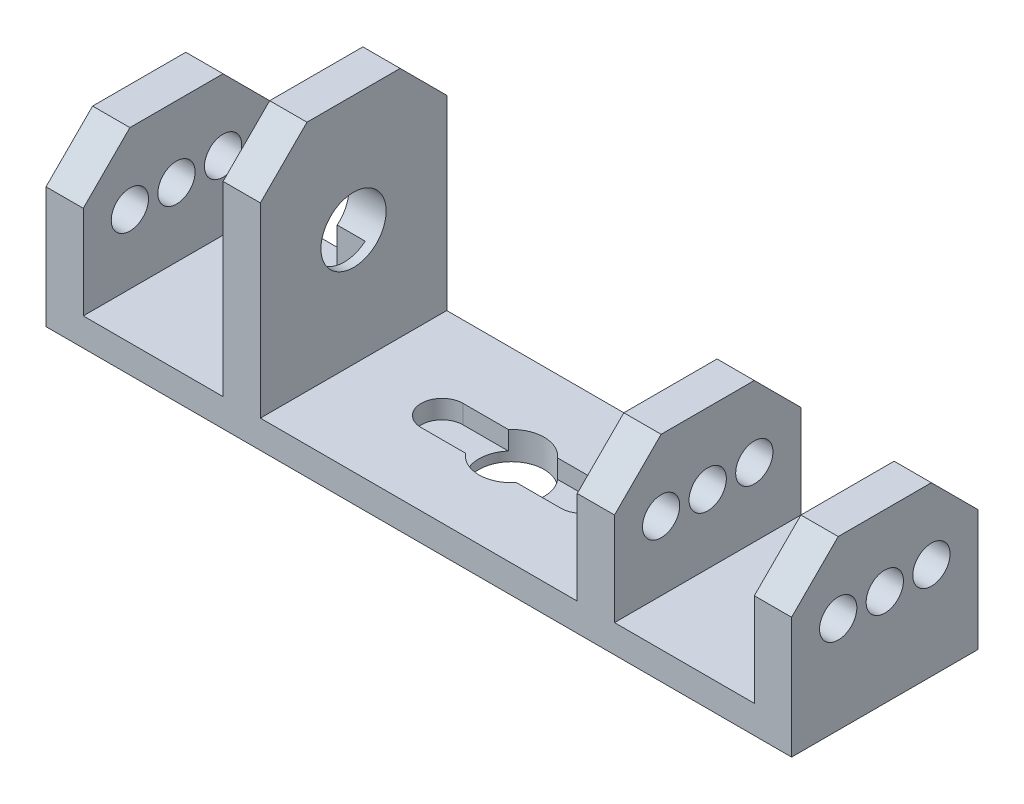
SolidWorks part; units mm, degrees
ref_plane "前视基准面" through (0, 0, 0) normal (0, 0, 1) x (1, 0, 0)
ref_plane "上视基准面" through (0, 0, 0) normal (0, 1, 0) x (1, 0, 0)
ref_plane "右视基准面" through (0, 0, 0) normal (1, 0, 0) x (0, 0, -1)
sketch "草图1" plane through (0, 0, 0) normal (0, 1, 0) x (1, 0, 0)
  line L1 (0, 0) -> (80, 0)
  line L2 (0, 0) -> (0, -20)
  line L3 (0, -20) -> (80, -20)
  line L4 (80, 0) -> (80, -20)
  dimension "D1" = 80
  dimension "D2" = 20
extrude "凸台-拉伸1" add sketch "草图1" along normal blind 3
sketch "草图2" plane through (0, 3, 0) normal (0, 1, 0) x (1, 0, 0)
  line L0 (0, 0) -> (0, -20) construction
  circle A0 centre (40, -10.0455) radius 3.5
  dimension "D1" = 7
  dimension "D2" = 40
extrude "切除-拉伸1" cut sketch "草图2" against normal blind 3
sketch "草图3" plane through (0, 3, 0) normal (0, 1, 0) x (1, 0, 0)
  line L0 (80, 0) -> (0, 0) construction
  line L1 (32.5, -7.75) -> (47.5, -7.75)
  line L2 (32.5, -7.75) -> (32.5, -12.25)
  line L3 (32.5, -12.25) -> (47.5, -12.25)
  line L4 (47.5, -7.75) -> (47.5, -12.25)
  circle A0 centre (40, -10.0455) radius 3.5 construction
  dimension "D1" = 4.5
  dimension "D2" = 7.75
  dimension "D3" = 15
  dimension "D4" = 7.5
extrude "切除-拉伸2" cut sketch "草图3" against normal blind 2
sketch "草图5" plane through (0, 3, 0) normal (0, 1, 0) x (1, 0, 0)
  line L0 (32.5, -7.75) -> (32.5, -12.25) construction
  line L1 (47.5, -12.25) -> (47.5, -7.75) construction
  circle A0 centre (32.5, -10) radius 2.25
  circle A1 centre (47.5, -10) radius 2.25
  dimension "D1" = 4.5
extrude "切除-拉伸3" cut sketch "草图5" against normal blind 2
sketch "草图6" plane through (0, 3, 0) normal (0, 1, 0) x (1, 0, 0)
  line L0 (0, -20) -> (80, -20) construction
  line L1 (0, 0) -> (4, 0)
  line L2 (0, 0) -> (0, -20)
  line L3 (0, -20) -> (4, -20)
  line L4 (4, 0) -> (4, -20)
  line L5 (80, 0) -> (0, 0) construction
  line L6 (80, 0) -> (76, 0)
  line L7 (80, 0) -> (80, -20)
  line L8 (80, -20) -> (76, -20)
  line L9 (76, 0) -> (76, -20)
  line L15 (57, 0) -> (61, 0)
  line L16 (57, 0) -> (57, -20)
  line L17 (57, -20) -> (61, -20)
  line L18 (61, 0) -> (61, -20)
  dimension "D1" = 4
  dimension "D2" = 4
  dimension "D4" = 4
  dimension "D6" = 15
extrude "凸台-拉伸2" add sketch "草图6" along normal blind 15
sketch "草图7" plane through (80, 0, 0) normal (1, 0, 0) x (0, 0, -1)
  line L0 (-20, 13) -> (-15, 18)
  line L1 (-20, 18) -> (-20, 0) construction
  line L2 (-20, 18) -> (0, 18) construction
  line L3 (-15, 18) -> (-20, 18)
  line L4 (-20, 18) -> (-20, 13)
  line L5 (0, 13) -> (0, 18)
  line L6 (0, 18) -> (0, 0) construction
  line L7 (0, 18) -> (-5, 18)
  line L8 (-5, 18) -> (0, 13)
  dimension "D1" = 5
extrude "切除-拉伸4" cut sketch "草图7" against normal blind 83
sketch "草图8" plane through (0, 0, 0) normal (-1, 0, 0) x (0, 0, 1)
  line L0 (5, 10.3869) -> (0, 10.3869) construction
  line L1 (0, 13) -> (0, 0) construction
  line L2 (5, 10.3869) -> (10, 10.3869) construction
  line L3 (10, 10.3869) -> (15, 10.3869) construction
  line L4 (15, 10.3869) -> (20, 10.3869) construction
  line L5 (20, 13) -> (20, 0) construction
  circle A0 centre (5, 10.3869) radius 2
  circle A1 centre (10, 10.3869) radius 2
  circle A2 centre (15, 10.3869) radius 2
extrude "切除-拉伸5" cut sketch "草图8" against normal blind 83
sketch "草图9" plane through (0, 3, 0) normal (0, 1, 0) x (1, 0, 0)
  line L1 (57, 0) -> (4, 0) construction
  line L2 (19, 0) -> (23, 0)
  line L3 (19, 0) -> (19, -20)
  line L4 (19, -20) -> (23, -20)
  line L6 (23, 0) -> (23, -20)
  line L7 (4, -20) -> (57, -20) construction
  line L8 (4, -20) -> (4, 0) construction
  point P10 (4, -10)
  dimension "D1" = 4
  dimension "D2" = 15
extrude "凸台-拉伸3" add sketch "草图9" along normal blind 25
sketch "草图10" plane through (19, 0, 0) normal (-1, 0, 0) x (0, 0, 1)
  line L1 (0, 28) -> (20, 28) construction
  line L2 (0, 28) -> (0, 3) construction
  circle A0 centre (10, 15.5) radius 3.5
  dimension "D1" = 7
  dimension "D2" = 12.5
  dimension "D3" = 10
extrude "切除-拉伸6" cut sketch "草图10" against normal blind 6
sketch "草图11" plane through (19, 0, 0) normal (-1, 0, 0) x (0, 0, 1)
  line L0 (0, 28) -> (20, 28) construction
  line L1 (7.75, 7.9) -> (12.25, 7.9)
  line L2 (7.75, 7.9) -> (7.75, 22.9)
  line L3 (7.75, 22.9) -> (12.25, 22.9)
  line L4 (12.25, 7.9) -> (12.25, 22.9)
  line L6 (0, 28) -> (0, 3) construction
  dimension "D1" = 15
  dimension "D2" = 4.5
  dimension "D3" = 5.1
  dimension "D4" = 7.75
extrude "切除-拉伸7" cut sketch "草图11" against normal blind 3
sketch "草图12" plane through (19, 0, 0) normal (-1, 0, 0) x (0, 0, 1)
  line L0 (12.25, 22.9) -> (7.75, 22.9) construction
  line L1 (7.75, 7.9) -> (12.25, 7.9) construction
  circle A0 centre (10, 22.9) radius 2.25
  circle A1 centre (10, 7.9) radius 2.25
  dimension "D1" = 4.5
extrude "切除-拉伸8" cut sketch "草图12" against normal blind 3
sketch "草图13" plane through (19, 0, 0) normal (-1, 0, 0) x (0, 0, 1)
  line L0 (5, 28) -> (0, 23)
  line L1 (0, 28) -> (20, 28) construction
  line L2 (0, 28) -> (0, 3) construction
  line L3 (0, 23) -> (0, 28)
  line L4 (0, 28) -> (5, 28)
  line L5 (20, 28) -> (15, 28)
  line L6 (15, 28) -> (20, 23)
  line L7 (20, 28) -> (20, 3) construction
  line L8 (20, 23) -> (20, 28)
  dimension "D1" = 5
extrude "切除-拉伸9" cut sketch "草图13" against normal blind 10
